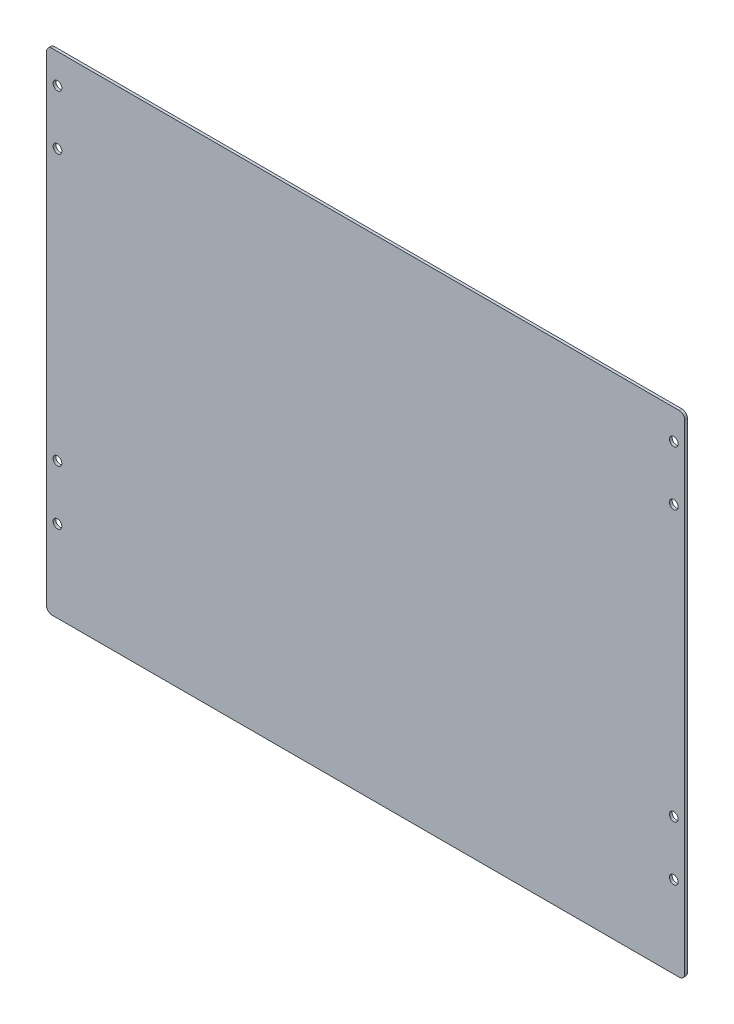
SolidWorks part; units mm, degrees
material "Thornel Mat VMA"
ref_plane "前视基准面" through (0, 0, 0) normal (0, 0, 1) x (1, 0, 0)
ref_plane "上视基准面" through (0, 0, 0) normal (0, 1, 0) x (1, 0, 0)
ref_plane "右视基准面" through (0, 0, 0) normal (1, 0, 0) x (0, 0, -1)
other "Configuration Table"
sketch "草图1" plane through (0, 0, 0) normal (0, 0, 1) x (1, 0, 0)
  line L1 (-117, 90) -> (117, 90)
  line L2 (-117, 90) -> (-117, -90)
  line L3 (-117, -90) -> (117, -90)
  line L4 (117, 90) -> (117, -90)
  line L5 (-117, 90) -> (117, -90) construction
  line L6 (-117, -90) -> (117, 90) construction
  point P0 (0, 0)
  dimension "D1" = 180
  dimension "D2" = 234
extrude "凸台-拉伸1" add sketch "草图1" along normal blind 1
sketch "草图2" plane through (0, 0, 1) normal (0, 0, 1) x (1, 0, 0)
  line L0 (-113, 90) -> (-113, -90) construction
  line L1 (117, 90) -> (-117, 90) construction
  line L2 (-117, -90) -> (117, -90) construction
  line L3 (-117, 90) -> (-117, -90) construction
  line L4 (0, 0) -> (0, -50000) construction
  circle A0 centre (-113, -60) radius 1.6
  circle A1 centre (-113, -40) radius 1.6
  circle A2 centre (-113, 59.12) radius 1.6
  circle A3 centre (-113, 79.12) radius 1.6
  circle A4 centre (113, -60) radius 1.6
  circle A5 centre (113, -40) radius 1.6
  circle A6 centre (113, 59.12) radius 1.6
  circle A7 centre (113, 79.12) radius 1.6
  dimension "D2" = 3.2
  dimension "D3" = 20
  dimension "D4" = 20
  dimension "D6" = 30
  dimension "D1" = 4
  dimension "D5" = 10.88
extrude "切除-拉伸1" cut sketch "草图2" against normal blind 10
fillet "圆角1" radius 2 4 edges at (117, -90, 0.5) (-117, -90, 0.5) (117, 90, 0.5) (-117, 90, 0.5)
